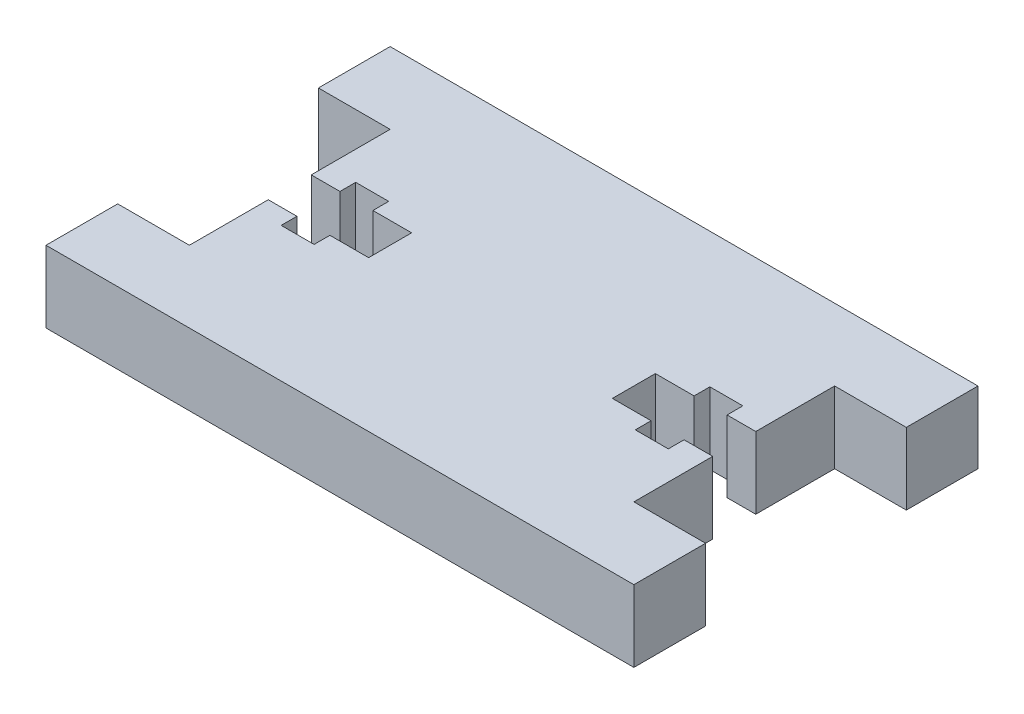
SolidWorks part; units mm, degrees
ref_plane "Front Plane" through (0, 0, 0) normal (0, 0, 1) x (1, 0, 0)
ref_plane "Top Plane" through (0, 0, 0) normal (0, 1, 0) x (1, 0, 0)
ref_plane "Right Plane" through (0, 0, 0) normal (1, 0, 0) x (0, 0, -1)
sketch "Sketch1" plane through (0, 0, 0) normal (0, 1, 0) x (1, 0, 0)
  line L0 (51.3755, 21.289) -> (44.3755, 18.289) construction
  line L1 (44.3755, 7.789) -> (75.3755, 7.789)
  line L2 (44.3755, 31.789) -> (75.3755, 31.789)
  line L3 (75.3755, 12.789) -> (75.3755, 18.289)
  line L4 (59.8755, 31.789) -> (59.8755, 7.789) construction
  line L5 (51.3755, 18.289) -> (44.3755, 21.289) construction
  line L6 (44.3755, 7.789) -> (39.3755, 7.789)
  line L7 (39.3755, 7.789) -> (39.3755, 12.789)
  line L8 (44.3755, 12.789) -> (44.3755, 18.289)
  line L9 (71.0755, 17.189) -> (73.3755, 17.189)
  line L10 (68.3755, 18.289) -> (71.0755, 18.289)
  line L11 (68.3755, 18.289) -> (68.3755, 21.289)
  line L12 (68.3755, 21.289) -> (71.0755, 21.289)
  line L13 (68.3755, 18.289) -> (75.3755, 21.289) construction
  line L14 (68.3755, 21.289) -> (75.3755, 18.289) construction
  line L15 (71.0755, 21.289) -> (71.0755, 22.389)
  line L16 (71.0755, 22.389) -> (73.3755, 22.389)
  line L17 (73.3755, 21.289) -> (73.3755, 22.389)
  line L18 (73.3755, 18.289) -> (73.3755, 17.189)
  line L19 (71.0755, 18.289) -> (71.0755, 17.189)
  line L20 (73.3755, 21.289) -> (75.3755, 21.289)
  line L21 (73.3755, 18.289) -> (75.3755, 18.289)
  line L22 (75.3755, 21.289) -> (75.3755, 26.789)
  line L23 (75.3755, 12.789) -> (80.3755, 12.789)
  line L24 (75.3755, 31.789) -> (80.3755, 31.789)
  line L25 (75.3755, 26.789) -> (80.3755, 26.789)
  line L26 (80.3755, 31.789) -> (80.3755, 26.789)
  line L27 (80.3755, 7.789) -> (80.3755, 12.789)
  line L28 (75.3755, 7.789) -> (80.3755, 7.789)
  line L29 (39.3755, 31.789) -> (39.3755, 26.789)
  line L30 (44.3755, 26.789) -> (39.3755, 26.789)
  line L31 (44.3755, 31.789) -> (39.3755, 31.789)
  line L32 (44.3755, 12.789) -> (39.3755, 12.789)
  line L33 (44.3755, 21.289) -> (44.3755, 26.789)
  line L34 (46.3755, 18.289) -> (44.3755, 18.289)
  line L35 (46.3755, 21.289) -> (44.3755, 21.289)
  line L36 (48.6755, 18.289) -> (48.6755, 17.189)
  line L37 (46.3755, 18.289) -> (46.3755, 17.189)
  line L38 (46.3755, 21.289) -> (46.3755, 22.389)
  line L39 (48.6755, 22.389) -> (46.3755, 22.389)
  line L40 (48.6755, 21.289) -> (48.6755, 22.389)
  line L41 (51.3755, 21.289) -> (48.6755, 21.289)
  line L42 (51.3755, 18.289) -> (51.3755, 21.289)
  line L43 (51.3755, 18.289) -> (48.6755, 18.289)
  line L44 (48.6755, 17.189) -> (46.3755, 17.189)
  line L45 (68.3755, 19.789) -> (59.8755, 19.789) construction
  point P23 (47.8755, 19.789)
  point P25 (71.8755, 19.789)
  point P44 (59.8755, 19.789)
  dimension "D2" = 31
  dimension "D3" = 3
  dimension "D4" = 5
  dimension "D5" = 5
  dimension "D6" = 2
  dimension "D7" = 2.3
  dimension "D8" = 2.7
  dimension "D9" = 1.1
  dimension "D10" = 5
  dimension "D11" = 24
extrude "Boss-Extrude1" add sketch "Sketch1" along normal blind 5
